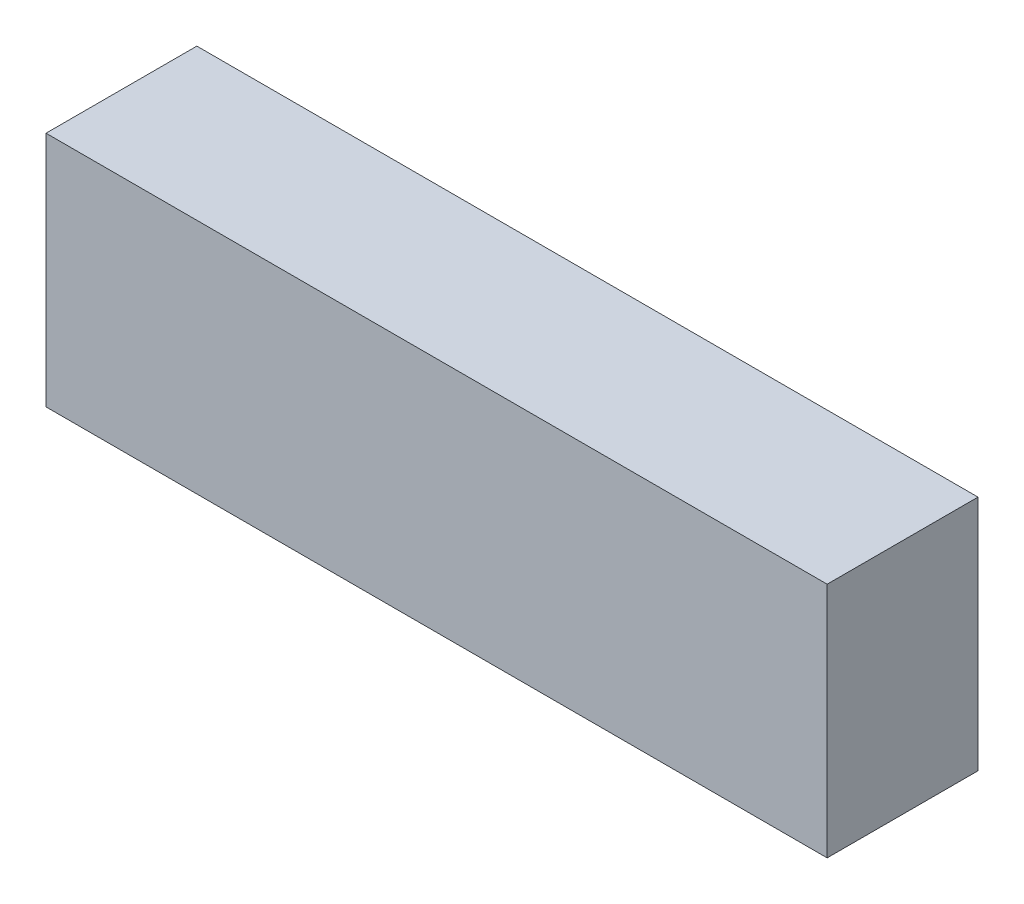
SolidWorks part; units mm, degrees
ref_plane "Front Plane" through (0, 0, 0) normal (0, 0, 1) x (1, 0, 0)
ref_plane "Top Plane" through (0, 0, 0) normal (0, 1, 0) x (1, 0, 0)
ref_plane "Right Plane" through (0, 0, 0) normal (1, 0, 0) x (0, 0, -1)
sketch "Sketch1" plane through (0, 0, 0) normal (0, 0, 1) x (1, 0, 0)
  line L1 (72.5, -22) -> (-72.5, -22)
  line L2 (72.5, -22) -> (72.5, 22)
  line L3 (72.5, 22) -> (-72.5, 22)
  line L4 (-72.5, -22) -> (-72.5, 22)
  line L5 (72.5, -22) -> (-72.5, 22) construction
  line L6 (72.5, 22) -> (-72.5, -22) construction
  point P0 (0, 0)
  dimension "D1" = 145
  dimension "D2" = 44
extrude "Boss-Extrude1" add sketch "Sketch1" along normal blind 28
